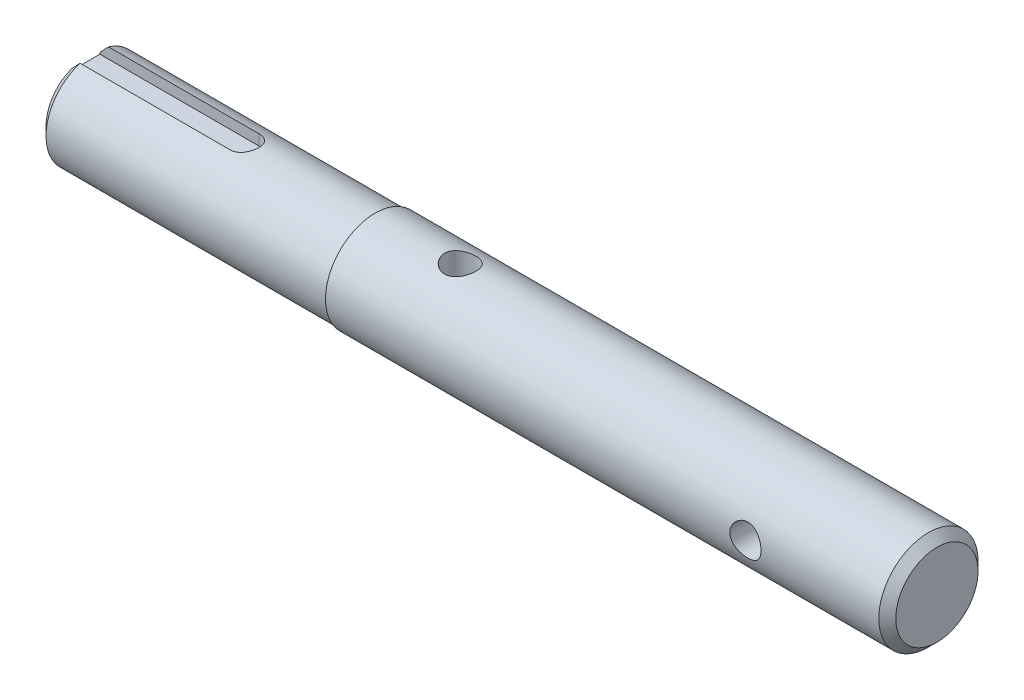
SolidWorks part; units mm, degrees
ref_plane "Front Plane" through (0, 0, 0) normal (0, 0, 1) x (1, 0, 0)
ref_plane "Top Plane" through (0, 0, 0) normal (0, 1, 0) x (1, 0, 0)
ref_plane "Right Plane" through (0, 0, 0) normal (1, 0, 0) x (0, 0, -1)
sketch "Sketch1" plane through (0, 0, 0) normal (0, 0, 1) x (1, 0, 0)
  line L0 (0, 0) -> (300, 0)
  line L1 (300, 0) -> (300, 17.5)
  line L2 (300, 17.5) -> (102, 17.5)
  line L3 (102, 17.5) -> (102, 17)
  line L4 (102, 17) -> (0, 17)
  line L5 (0, 17) -> (0, 0)
  dimension "D1" = 17.5
  dimension "D2" = 17
  dimension "D3" = 300
  dimension "D4" = 102
revolve "Revolve1" add sketch "Sketch1" angle 360 about L0
chamfer "Chamfer1" distance 3 angle 45 2 edges at (0, 0, 17) (300, 0, 17.5)
sketch "Sketch2" plane through (0, 0, 0) normal (0, 1, 0) x (1, 0, 0)
  line L0 (0, 14) -> (0, -14) construction
  line L1 (0, 5) -> (56, 5)
  line L2 (0, 5) -> (0, -5)
  line L3 (0, -5) -> (56, -5)
  line L4 (56, 5) -> (56, -5) construction
  line L5 (0, 5) -> (56, -5) construction
  line L6 (0, -5) -> (56, 5) construction
  arc A0 (56, 5) -> (56, -5) centre (56, 0) cw
  point P4 (28, 0)
  dimension "D4" = 5
  dimension "D1" = 56
  dimension "D2" = 5
  dimension "D3" = 10
extrude "Cut-Extrude1" cut sketch "Sketch2" against normal blind 4.5 from offset 17
sketch "Sketch3" plane through (0, 0, 0) normal (0, 1, 0) x (1, 0, 0)
  circle A0 centre (132, 0) radius 5.5
  dimension "D1" = 11
  dimension "D2" = 132
extrude "Cut-Extrude2" cut sketch "Sketch3" against normal through all both and the other way through all
sketch "Sketch4" plane through (0, 0, 0) normal (0, 0, 1) x (1, 0, 0)
  circle A0 centre (250, 0) radius 5.5
  dimension "D1" = 11
  dimension "D2" = 250
extrude "Cut-Extrude3" cut sketch "Sketch4" against normal through all both and the other way through all
